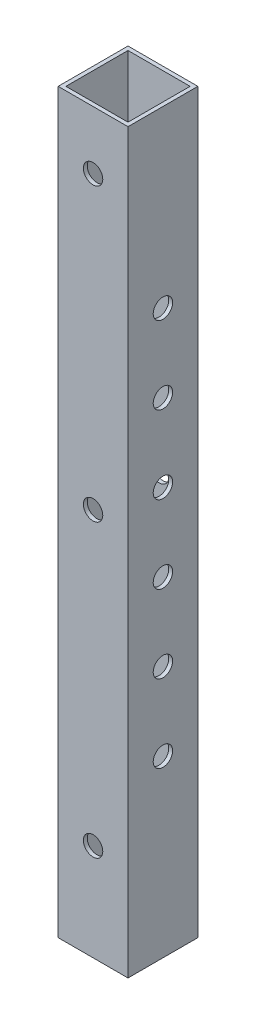
SolidWorks part; units mm, degrees
material "Alloy Steel"
ref_plane "Front Plane" through (0, 0, 0) normal (0, 0, 1) x (1, 0, 0)
ref_plane "Top Plane" through (0, 0, 0) normal (0, 1, 0) x (1, 0, 0)
ref_plane "Right Plane" through (0, 0, 0) normal (1, 0, 0) x (0, 0, -1)
sketch "Sketch1" plane through (0, 0, 0) normal (0, 0, 1) x (1, 0, 0)
  line L1 (0, 0) -> (45.72, 0)
  line L2 (0, 0) -> (0, -482.6)
  line L3 (0, -482.6) -> (45.72, -482.6)
  line L4 (45.72, 0) -> (45.72, -482.6)
  dimension "D1" = 45.72
  dimension "D2" = 482.6
extrude "Boss-Extrude1" add sketch "Sketch1" along normal blind 45.72
shell "Shell1" thickness 2.54
sketch "Sketch5" plane through (0, -482.6, 0) normal (0, -1, 0) x (1, 0, 0)
  line L0 (43.18, 43.18) -> (2.54, 43.18)
  line L1 (2.54, 43.18) -> (2.54, 2.54)
  line L2 (2.54, 2.54) -> (43.18, 2.54)
  line L3 (43.18, 2.54) -> (43.18, 43.18)
extrude "Cut-Extrude1" cut sketch "Sketch5" against normal blind 2.54
hole_wizard "#97 (0.5) Diameter Hole1" positions "3DSketch1" profile "Sketch3" hole size "#97" standard "ANSI Inch" end condition through all
sketch3d "3DSketch1"
  line L0 (0, 0, 45.72) -> (0, -482.6, 45.72) construction
  line L1 (45.72, 0, 45.72) -> (0, 0, 45.72) construction
  point P0 (22.86, -38.1, 45.72)
  point P2 (22.86, -228.6, 45.72)
  point P9 (22.86, -419.1, 45.72)
  dimension "D1" = 22.86
  dimension "D2" = 22.86
  dimension "D3" = 38.1
  dimension "D4" = 190.5
  dimension "D5" = 22.86
  dimension "D6" = 190.5
sketch "Sketch3" plane through (22.86, -38.1, 45.72) normal (1, 0, 0) x (0, -1, 0)
  line L0 (0, 0) -> (0, 45.72)
  line L1 (0, 45.72) -> (6.35, 45.72)
  line L2 (6.35, 45.72) -> (6.35, 0)
  line L5 (6.35, 0) -> (0, 0)
  line L11 (0, -6.35) -> (0, 107.95) construction
  dimension "Thru Hole Dia." = 12.7
  dimension "Thru Hole Depth" = 45.72
hole_wizard "#97 (0.5) Diameter Hole2" positions "3DSketch2" profile "Sketch4" hole size "#97" standard "ANSI Inch" end condition through all
sketch3d "3DSketch2"
  line L0 (45.72, -482.6, 45.72) -> (45.72, 0, 45.72) construction
  line L1 (45.72, 0, 45.72) -> (45.72, 0, 0) construction
  line L2 (45.72, -482.6, 0) -> (45.72, 0, 0) construction
  point P0 (45.72, -114.3, 22.86)
  point P2 (45.72, -165.1, 22.86)
  point P9 (45.72, -215.9, 22.86)
  point P11 (45.72, -266.7, 22.86)
  point P13 (45.72, -317.5, 22.86)
  point P15 (45.72, -368.3, 22.86)
  dimension "D1" = 22.86
  dimension "D2" = 22.86
  dimension "D3" = 114.3
  dimension "D4" = 50.8
  dimension "D5" = 22.86
  dimension "D6" = 22.86
  dimension "D7" = 22.86
  dimension "D8" = 22.86
  dimension "D9" = 50.8
  dimension "D10" = 50.8
  dimension "D11" = 50.8
  dimension "D12" = 50.8
sketch "Sketch4" plane through (45.72, -114.3, 22.86) normal (0, 1, 0) x (0, 0, -1)
  line L0 (0, 0) -> (0, 45.72)
  line L1 (0, 45.72) -> (6.35, 45.72)
  line L2 (6.35, 45.72) -> (6.35, 0)
  line L5 (6.35, 0) -> (0, 0)
  line L11 (0, -6.35) -> (0, 107.95) construction
  dimension "Thru Hole Dia." = 12.7
  dimension "Thru Hole Depth" = 45.72
